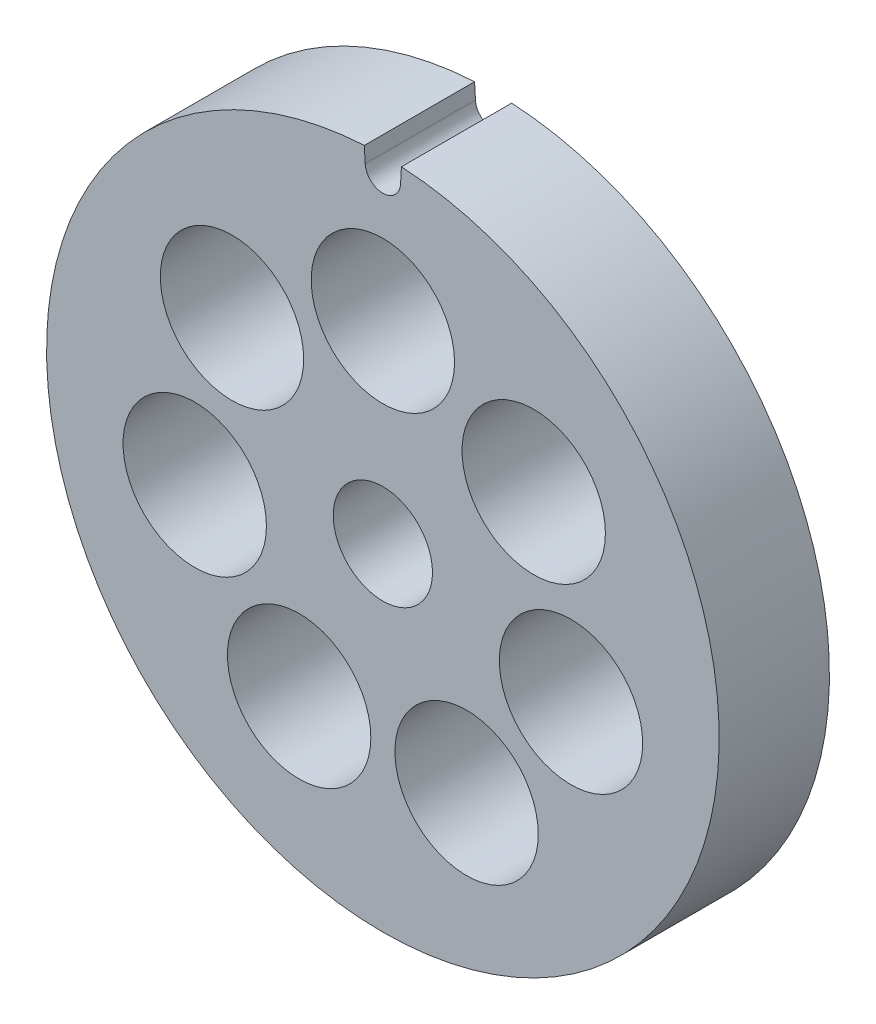
SolidWorks part; units mm, degrees
ref_plane "Płaszczyzna przednia" through (0, 0, 0) normal (0, 0, 1) x (1, 0, 0)
ref_plane "Płaszczyzna górna" through (0, 0, 0) normal (0, 1, 0) x (1, 0, 0)
ref_plane "Płaszczyzna prawa" through (0, 0, 0) normal (1, 0, 0) x (0, 0, -1)
sketch "Szkic1" plane through (0, 0, 0) normal (0, 0, 1) x (1, 0, 0)
  line L0 (0, 0) -> (0, 7.396) construction
  line L1 (0, 0) -> (0, 17.5) construction
  line L2 (0, 0) -> (-1.6806, 30.4537) construction
  line L3 (0, 0) -> (1.6806, 30.4537) construction
  line L4 (1.6806, 30.4537) -> (1.6034, 29.0537)
  line L5 (-1.6806, 30.4537) -> (-1.6034, 29.0537)
  arc A0 (-1.6806, 30.4537) -> (1.6806, 30.4537) centre (0, 0) ccw
  circle A1 centre (0, 0) radius 4.5
  circle A2 centre (0, 17.5) radius 6.5
  circle A3 centre (13.6821, 10.9111) radius 6.5
  circle A4 centre (17.0612, -3.8941) radius 6.5
  circle A5 centre (7.593, -15.767) radius 6.5
  circle A6 centre (-7.593, -15.767) radius 6.5
  circle A7 centre (-17.0612, -3.8941) radius 6.5
  circle A8 centre (-13.6821, 10.9111) radius 6.5
  arc A9 (-1.6034, 29.0537) -> (1.6034, 29.0537) centre (0, 29.1421) ccw
  point P30 (-1.6806, 30.4537)
  dimension "D1" = 61
  dimension "D2" = 9
  dimension "D3" = 13
  dimension "D7" = 3.159
  dimension "D9" = 1.4
  dimension "D4" = 17.5
  dimension "D6" = 17.5
  dimension "D8" = 1.4
  dimension "D5" = 7
sketch "Szkic2" plane through (0, 0, 0) normal (0, 0, 1) x (1, 0, 0)
extrude "Dodanie-wyciągnięcie1" add sketch "Szkic1" along normal blind 10
